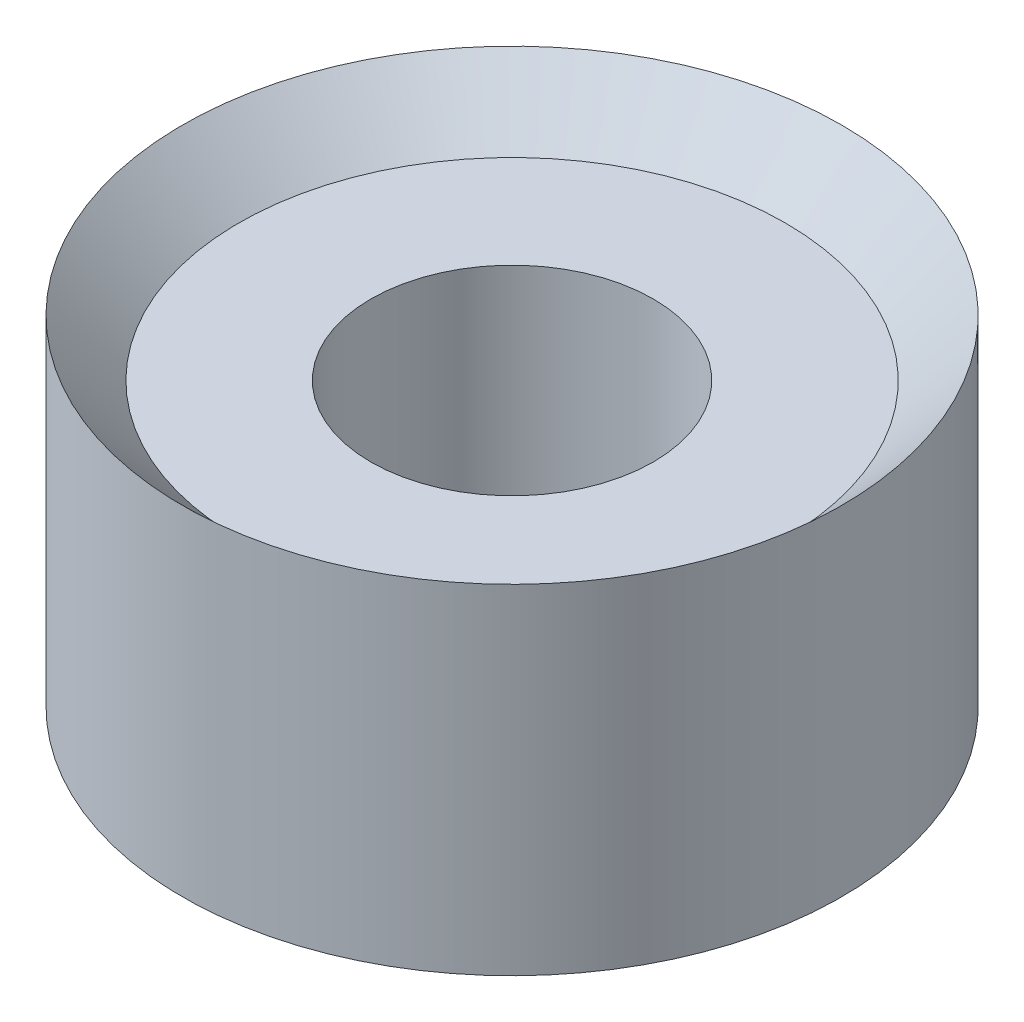
SolidWorks part; units mm, degrees
ref_plane "Front Plane" through (0, 0, 0) normal (0, 0, 1) x (1, 0, 0)
ref_plane "Top Plane" through (0, 0, 0) normal (0, 1, 0) x (1, 0, 0)
ref_plane "Right Plane" through (0, 0, 0) normal (1, 0, 0) x (0, 0, -1)
sketch "Sketch1" plane through (0, 0, 0) normal (0, 0, 1) x (1, 0, 0)
  line L0 (0, 0) -> (-7.5, 0) construction
  line L1 (-7.5, 0) -> (-17.5, 0)
  line L2 (-17.5, 0) -> (-17.5, 18)
  line L3 (-17.5, 18) -> (-14.5, 15)
  line L4 (-14.5, 15) -> (-7.5, 15)
  line L5 (-7.5, 15) -> (-7.5, 0)
  line L6 (-14.5, 15) -> (-17.5, 15) construction
  point P5 (-17.5, 18)
  dimension "D1" = 7.5
  dimension "D2" = 17.5
  dimension "D3" = 18
  dimension "D4" = 45
  dimension "D5" = 3
ref_axis "Axis1" through (0, -0.9, 0) along (0, 1, 0)
revolve "Revolve1" add sketch "Sketch1" angle 360 about axis through (0, -0.9, 0) along (0, 1, 0)
